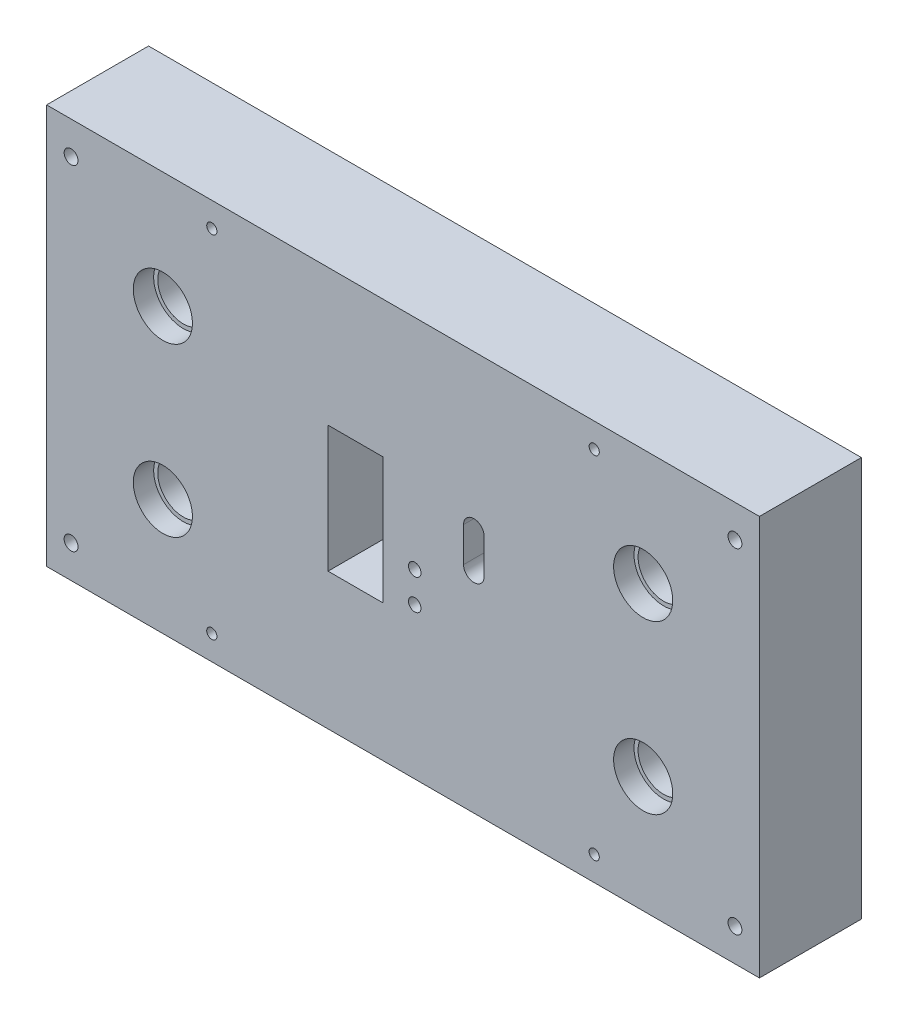
SolidWorks part; units mm, degrees
ref_plane "FP" through (0, 0, 0) normal (0, 0, 1) x (1, 0, 0)
ref_plane "TP" through (0, 0, 0) normal (0, 1, 0) x (1, 0, 0)
ref_plane "RP" through (0, 0, 0) normal (1, 0, 0) x (0, 0, -1)
sketch "Sketch2" plane through (0, 0, 0) normal (0, 0, 1) x (1, 0, 0)
  line L1 (-209.5, 98) -> (140, 98)
  line L2 (-209.5, 98) -> (-209.5, -98)
  line L3 (-209.5, -98) -> (140, -98)
  line L4 (140, 98) -> (140, -98)
  line L6 (-119.5, -79) -> (50, -79) construction
  line L7 (50, -79) -> (50, 79) construction
  line L9 (50, 79) -> (-119.5, 79) construction
  line L13 (-5.06, 22) -> (-5.06, 5)
  line L14 (5.06, 5) -> (5.06, 22)
  line L15 (-44.5, 31) -> (-71.5, 31)
  line L16 (-71.5, 31) -> (-71.5, -31)
  line L17 (-71.5, -31) -> (-44.5, -31)
  line L18 (-44.5, -31) -> (-44.5, 31)
  line L19 (-44.5, 31) -> (-71.5, 31)
  line L20 (-71.5, 31) -> (-71.5, -31)
  line L21 (-71.5, -31) -> (-44.5, -31)
  line L22 (-44.5, -31) -> (-44.5, 31)
  line L23 (-5.06, 22) -> (-5.06, 5)
  line L24 (5.06, 5) -> (5.06, 22)
  line L281 (-119.5, 79) -> (-119.5, -79) construction
  circle A1 centre (-29, -24) radius 3.06 construction
  circle A2 centre (-29, -24) radius 3.06
  circle A3 centre (-29, -9) radius 3.06 construction
  circle A4 centre (-29, -9) radius 3.06
  arc A8 (-5.06, 5) -> (5.06, 5) centre (0, 5) ccw
  arc A9 (5.06, 22) -> (-5.06, 22) centre (0, 22) ccw
  arc A10 (-5.06, 5) -> (5.06, 5) centre (0, 5) ccw
  arc A11 (5.06, 22) -> (-5.06, 22) centre (0, 22) ccw
  dimension "D1" = 90
  dimension "D2" = 19
  dimension "D3" = 90
  dimension "D4" = 19
  dimension "D5" = 0
  dimension "D6" = 0
extrude "Boss-Extrude1" add sketch "Sketch2" along normal blind 50
hole_wizard "M8x1.25 Tapped Hole2" positions "Sketch5" profile "Sketch6" tap size "M8x1.25" standard "ANSI Metric"
sketch "Sketch5" plane through (0, 0, 0) normal (0, 0, -1) x (-0.9063, -0.4226, 0)
  point P0 (74.6067, 94.3721)
  point P1 (120.2495, -3.5092)
  point P2 (-57.2611, 32.8811)
  point P3 (-11.6183, -65.0001)
cosmetic thread "Hole Thread5" parameters "D1"=16, "D2"=8
cosmetic thread "Hole Thread6" parameters "D1"=16, "D2"=8
cosmetic thread "Hole Thread7" parameters "D1"=16, "D2"=8
cosmetic thread "Hole Thread8" parameters "D1"=16, "D2"=8
sketch "Sketch6" plane through (-107.5, 54, 0) normal (1, 0, 0) x (0, 1, 0)
  line L0 (0, 0) -> (0, 22.0429)
  line L1 (0, 22.0429) -> (3.4, 20)
  line L2 (3.4, 20) -> (3.4, 0)
  line L3 (3.4, 0) -> (0, 0)
  line L4 (0, 22.0429) -> (-3.4, 20) construction
  line L5 (0, -6.35) -> (0, 107.95) construction
  dimension "Tap Drill Dia." = 6.8
  dimension "Tap Drill Depth" = 20
  dimension "Drill Angle" = 118
hole_wizard "M6x1.0 Tapped Hole1" positions "Sketch8" profile "Sketch9" tap size "M6x1.0" standard "ANSI Metric"
sketch "Sketch8" plane through (0, 0, 50) normal (0, 0, 1) x (0.9063, 0.4226, 0)
  point P0 (89.8173, 53.008)
  point P1 (17.127, -102.8769)
cosmetic thread "Hole Thread9" parameters "D1"=9, "D2"=6
cosmetic thread "Hole Thread10" parameters "D1"=9, "D2"=6
sketch "Sketch9" plane through (59, 86, 50) normal (1, 0, 0) x (0, -1, 0)
  line L0 (0, 0) -> (0, 21.5022)
  line L1 (0, 21.5022) -> (2.5, 20)
  line L2 (2.5, 20) -> (2.5, 0)
  line L5 (2.5, 0) -> (0, 0)
  line L10 (0, 21.5022) -> (-2.5, 20) construction
  line L11 (0, -6.35) -> (0, 107.95) construction
  dimension "Tap Drill Dia." = 5
  dimension "Tap Drill Depth" = 20
  dimension "Drill Angle" = 118
hole_wizard "M6x1.0 Tapped Hole2" positions "Sketch10" profile "Sketch11" tap size "M6x1.0" standard "ANSI Metric"
sketch "Sketch10" plane through (0, 0, 50) normal (0, 0, 1) x (0.9063, 0.4226, 0)
  point P0 (-80.1154, 132.2489)
  point P1 (-152.8057, -23.636)
cosmetic thread "Hole Thread11" parameters "D1"=12, "D2"=6
cosmetic thread "Hole Thread12" parameters "D1"=12, "D2"=6
sketch "Sketch11" plane through (-128.5, 86, 50) normal (1, 0, 0) x (0, -1, 0)
  line L0 (0, 0) -> (0, 21.5022)
  line L1 (0, 21.5022) -> (2.5, 20)
  line L2 (2.5, 20) -> (2.5, 0)
  line L5 (2.5, 0) -> (0, 0)
  line L10 (0, 21.5022) -> (-2.5, 20) construction
  line L11 (0, -6.35) -> (0, 107.95) construction
  dimension "Tap Drill Dia." = 5
  dimension "Tap Drill Depth" = 20
  dimension "Drill Angle" = 118
hole_wizard "M8x1.25 Tapped Hole4" positions "Sketch12" profile "Sketch13" tap size "M8x1.25" standard "ANSI Metric"
sketch "Sketch12" plane through (0, 0, 50) normal (0, 0, 1) x (0.9063, 0.4226, 0)
  point P0 (81.3527, -128.4124)
  point P1 (150.6621, 20.2221)
sketch "Sketch13" plane through (128, -82, 50) normal (1, 0, 0) x (0, -1, 0)
  line L0 (0, 0) -> (0, 22.0429)
  line L1 (0, 22.0429) -> (3.4, 20)
  line L2 (3.4, 20) -> (3.4, 0)
  line L3 (3.4, 0) -> (0, 0)
  line L4 (0, 22.0429) -> (-3.4, 20) construction
  line L5 (0, -6.35) -> (0, 107.95) construction
  dimension "Tap Drill Dia." = 6.8
  dimension "Tap Drill Depth" = 20
  dimension "Drill Angle" = 118
cosmetic thread "Hole Thread13" parameters "D1"=16, "D2"=8
cosmetic thread "Hole Thread14" parameters "D1"=16, "D2"=8
hole_wizard "M8x1.25 Tapped Hole5" positions "Sketch14" profile "Sketch15" tap size "M8x1.25" standard "ANSI Metric"
sketch "Sketch14" plane through (0, 0, 50) normal (0, 0, 1) x (0.9063, 0.4226, 0)
  point P0 (-144.3411, 157.7843)
  point P1 (-213.6505, 9.1499)
sketch "Sketch15" plane through (-197.5, 82, 50) normal (1, 0, 0) x (0, -1, 0)
  line L0 (0, 0) -> (0, 22.0429)
  line L1 (0, 22.0429) -> (3.4, 20)
  line L2 (3.4, 20) -> (3.4, 0)
  line L3 (3.4, 0) -> (0, 0)
  line L4 (0, 22.0429) -> (-3.4, 20) construction
  line L5 (0, -6.35) -> (0, 107.95) construction
  dimension "Tap Drill Dia." = 6.8
  dimension "Tap Drill Depth" = 20
  dimension "Drill Angle" = 118
cosmetic thread "Hole Thread15" parameters "D1"=16, "D2"=8
cosmetic thread "Hole Thread16" parameters "D1"=16, "D2"=8
hole_wizard "Hole1" positions "3DSketch1" profile "Sketch16" legacy
sketch3d "3DSketch1"
  circle A0 centre (83, -41, -179) radius 19 construction
  circle A1 centre (83, 41, -129) radius 17 construction
  circle A2 centre (-152.5, 41, -129) radius 17 construction
  circle A3 centre (-152.5, -41, -129) radius 17 construction
  point P0 (83, -41, 50)
  point P2 (83, 41, 50)
  point P4 (-152.5, 41, 50)
  point P6 (-152.5, -41, 50)
  point P11 (83, -41, -198)
  point P14 (83, 41, -146)
  point P17 (-152.5, 41, -146)
  point P20 (-152.5, -41, -146)
sketch "Sketch16" plane through (83, -41, 50) normal (1, 0, 0) x (0, -1, 0)
  line L0 (0, 0) -> (0, 70)
  line L1 (0, 70) -> (12.5, 70)
  line L2 (12.5, 70) -> (12.5, 10)
  line L3 (12.5, 10) -> (14.5, 10)
  line L4 (14.5, 10) -> (14.5, 0)
  line L5 (14.5, 0) -> (0, 0)
  line L6 (0, 110) -> (0, -10) construction
  dimension "Diameter" = 25
  dimension "Depth" = 70
  dimension "C-Bore Diameter" = 29
  dimension "C-Bore Depth" = 10
hole_wizard "M8x1.25 Tapped Hole1" positions "Sketch3" profile "Sketch4" tap size "M8x1.25" standard "ANSI Metric"
sketch "Sketch3" plane through (0, 0, 50) normal (0, 0, 1) x (0.9063, 0.4226, 0)
  point P0 (62.4986, -109.6901)
  point P1 (124.2008, 22.6308)
  point P2 (-187.1892, 6.7412)
  point P3 (-125.487, 139.0621)
sketch "Sketch4" plane through (103, -73, 50) normal (1, 0, 0) x (0, -1, 0)
  line L0 (0, 0) -> (0, 14.0429)
  line L1 (0, 14.0429) -> (3.4, 12)
  line L2 (3.4, 12) -> (3.4, 0)
  line L3 (3.4, 0) -> (0, 0)
  line L4 (0, 14.0429) -> (-3.4, 12) construction
  line L5 (0, -6.35) -> (0, 107.95) construction
  dimension "Tap Drill Dia." = 6.8
  dimension "Tap Drill Depth" = 12
  dimension "Drill Angle" = 118
cosmetic thread "Hole Thread1" parameters "D1"=10.75, "D2"=8
cosmetic thread "Hole Thread2" parameters "D1"=10.75, "D2"=8
cosmetic thread "Hole Thread3" parameters "D1"=10.75, "D2"=8
cosmetic thread "Hole Thread4" parameters "D1"=10.75, "D2"=8
